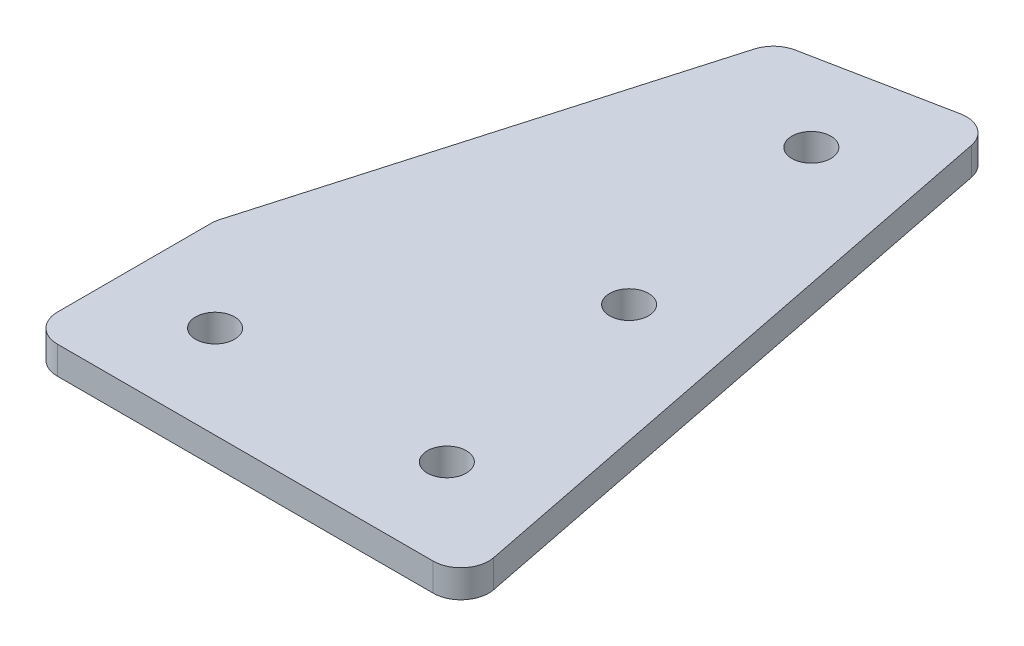
SolidWorks part; units mm, degrees
material "A-玻璃纤维"
ref_plane "前视基准面" through (0, 0, 0) normal (0, 0, 1) x (1, 0, 0)
ref_plane "上视基准面" through (0, 0, 0) normal (0, 1, 0) x (1, 0, 0)
ref_plane "右视基准面" through (0, 0, 0) normal (1, 0, 0) x (0, 0, -1)
sketch "草图1" plane through (0, 0, 0) normal (0, 1, 0) x (1, 0, 0)
  line L0 (-35, 0) -> (35, 0) construction
  line L1 (0, 0) -> (-11.6746, 58.8532) construction
  line L2 (8.2112, 10) -> (-1.8657, 60.799)
  line L3 (-35, -10) -> (35, -10)
  line L4 (9.8089, 1.9458) -> (-1.8657, 60.799) construction
  line L5 (-35, 10) -> (35, 10)
  line L6 (-12.1785, 10) -> (-21.4835, 56.9075)
  line L7 (35, 10) -> (35, -10)
  line L8 (-35, 10) -> (-35, -10)
  line L9 (-1.8657, 60.799) -> (-21.4835, 56.9075)
  line L10 (-21.4835, 56.9075) -> (-35, 10)
  line L11 (-1.8657, 60.799) -> (35, 10)
  line L12 (8.2112, 10) -> (12.1785, -10)
  circle A0 centre (0, 0) radius 2.1
  circle A1 centre (25, 0) radius 2.1
  circle A2 centre (-4.8644, 24.5222) radius 2.1
  circle A3 centre (-9.7288, 49.0444) radius 2.1
  circle A4 centre (-25, 0) radius 2.1
  dimension "D2" = 4.2
  dimension "D3" = 25
  dimension "D4" = 25
  dimension "D5" = 25
  dimension "D6" = 25
  dimension "D10" = 10
  dimension "D1" = 78.78
  dimension "D9" = 10
  dimension "D11" = 10
  dimension "D7" = 10
  dimension "D8" = 10
extrude "凸台-拉伸1" add sketch "草图1" along normal blind 3 contours L2 L9 L6 L5 A3 A2 | L12 L5 L8 L3 A4 A0 | L6 L10 L5
fillet "圆角1" radius 3 5 edges at (-35, 1.5, 10) (-35, 1.5, -10) (-21.4835, 1.5, -56.9075) (12.1785, 1.5, 10) (-1.8657, 1.5, -60.799)
